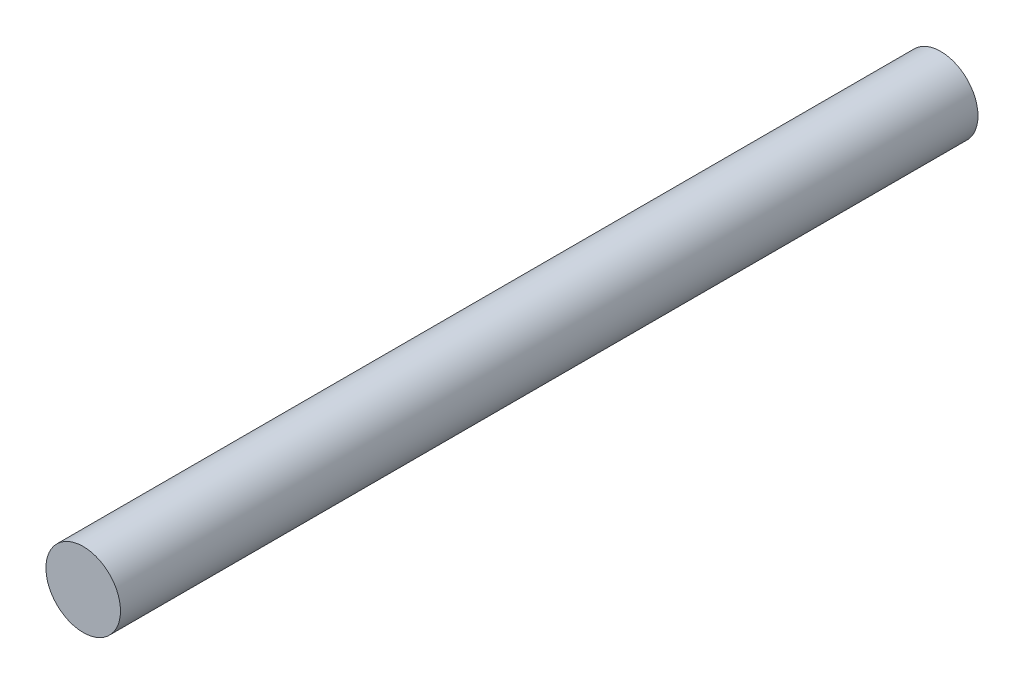
SolidWorks part; units mm, degrees
ref_plane "Piano frontale" through (0, 0, 0) normal (0, 0, 1) x (1, 0, 0)
ref_plane "Piano superiore" through (0, 0, 0) normal (0, 1, 0) x (1, 0, 0)
ref_plane "Piano destro" through (0, 0, 0) normal (1, 0, 0) x (0, 0, -1)
sketch "Schizzo1" plane through (0, 0, 0) normal (0, 0, 1) x (1, 0, 0)
  circle A0 centre (0, 0) radius 2
  dimension "D1" = 4
extrude "Estrusione-Estrusione1" add sketch "Schizzo1" along normal blind 46
